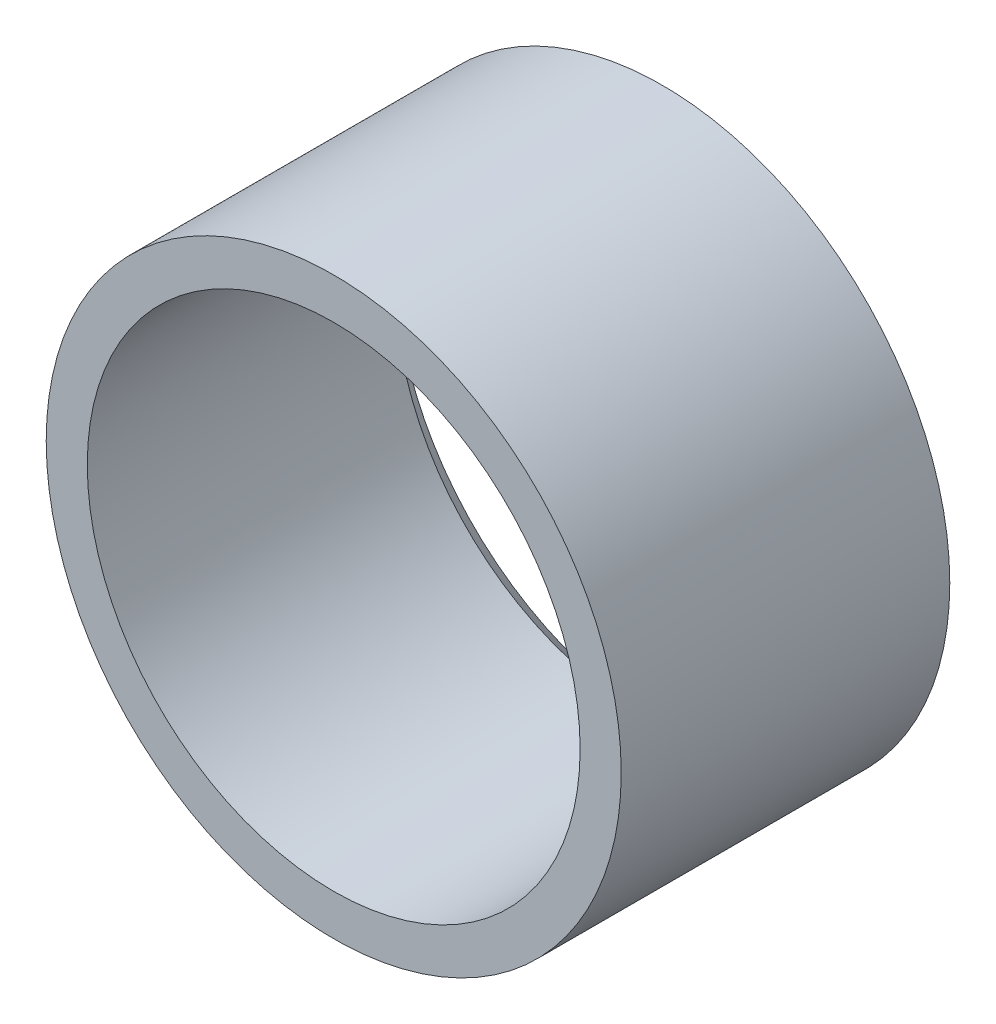
SolidWorks part; units mm, degrees
ref_plane "前视基准面" through (0, 0, 0) normal (0, 0, 1) x (1, 0, 0)
ref_plane "上视基准面" through (0, 0, 0) normal (0, 1, 0) x (1, 0, 0)
ref_plane "右视基准面" through (0, 0, 0) normal (1, 0, 0) x (0, 0, -1)
sketch "草图1" plane through (0, 0, 0) normal (0, 0, 1) x (1, 0, 0)
  circle A0 centre (0, 0) radius 6
  circle A1 centre (0, 0) radius 7
  dimension "D1" = 12
  dimension "D2" = 14
extrude "凸台-拉伸1" add sketch "草图1" along normal blind 8
chamfer "倒角1" distance 0.5 angle 45 1 edges at (6, 0, 0)
